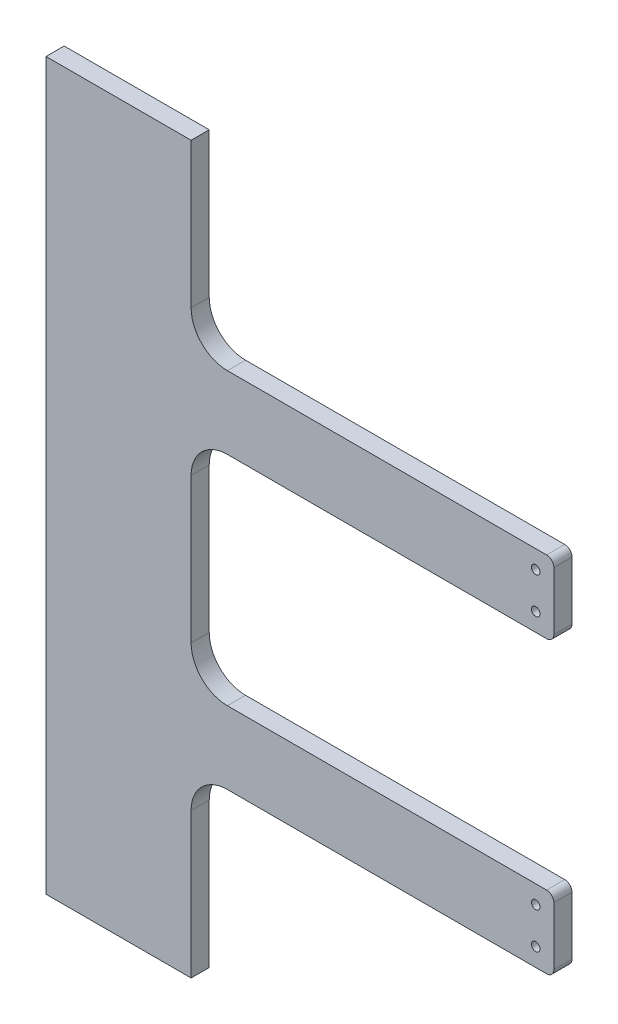
SolidWorks part; units mm, degrees
material "Pin"
ref_plane "Front" through (0, 0, 0) normal (0, 0, 1) x (1, 0, 0)
ref_plane "Top" through (0, 0, 0) normal (0, 1, 0) x (1, 0, 0)
ref_plane "Right" through (0, 0, 0) normal (1, 0, 0) x (0, 0, -1)
sketch "Esquisse1" plane through (0, 0, 0) normal (0, 0, 1) x (1, 0, 0)
  line L1 (-25.4, 127) -> (25.4, 127)
  line L2 (-25.4, 127) -> (-25.4, -127)
  line L3 (-25.4, -127) -> (25.4, -127)
  line L4 (25.4, 127) -> (25.4, -127)
  line L5 (-25.4, 127) -> (25.4, -127) construction
  line L6 (-25.4, -127) -> (25.4, 127) construction
  point P0 (0, 0)
  dimension "D1" = 254
  dimension "D2" = 50.8
extrude "Boss.-Extru.1" add sketch "Esquisse1" along normal blind 6.35
sketch "Esquisse2" plane through (0, 0, 6.35) normal (0, 0, 1) x (1, 0, 0)
  line L0 (25.4, -127) -> (25.4, 127) construction
  line L1 (25.4, -63.5) -> (152.4, -63.5)
  line L2 (25.4, -63.5) -> (25.4, -38.1)
  line L3 (25.4, -38.1) -> (152.4, -38.1)
  line L4 (152.4, -63.5) -> (152.4, -38.1)
  line L6 (-25.4, -127) -> (25.4, -127) construction
  line L7 (25.4, -38.1) -> (152.4, -63.5) construction
  line L8 (25.4, 38.1) -> (152.4, 38.1)
  line L9 (25.4, 38.1) -> (25.4, 63.5)
  line L10 (25.4, 63.5) -> (152.4, 63.5)
  line L11 (152.4, 38.1) -> (152.4, 63.5)
  line L12 (152.4, -38.1) -> (25.4, -63.5) construction
  line L13 (25.4, 63.5) -> (152.4, 38.1) construction
  line L14 (152.4, 63.5) -> (25.4, 38.1) construction
  point P12 (88.9, -50.8)
  point P13 (88.9, 50.8)
  dimension "D1" = 127
  dimension "D2" = 25.4
  dimension "D3" = 76.2
  dimension "D4" = 25.4
  dimension "D5" = 127
  dimension "D6" = 101.6
extrude "Boss.-Extru.2" add sketch "Esquisse2" against normal blind 6.35
fillet "Congé1" radius 12.7 4 edges at (25.4, -38.1, 3.175) (25.4, -63.5, 3.175) (25.4, 63.5, 3.175) (25.4, 38.1, 3.175)
fillet "Congé2" radius 2.54 4 edges at (152.4, 63.5, 3.175) (152.4, 38.1, 3.175) (152.4, -38.1, 3.175) (152.4, -63.5, 3.175)
sketch "Esquisse3" plane through (0, 0, 0) normal (0, 0, -1) x (-1, 0, 0)
  line L0 (-152.4, 40.64) -> (-152.4, 60.96) construction
  line L1 (-149.86, 63.5) -> (-38.1, 63.5) construction
  line L2 (-38.1, 38.1) -> (-149.86, 38.1) construction
  line L3 (-149.86, -38.1) -> (-38.1, -38.1) construction
  line L4 (-38.1, -63.5) -> (-149.86, -63.5) construction
  circle A0 centre (-146.05, 57.15) radius 1.5
  circle A1 centre (-146.05, 44.45) radius 1.5
  circle A2 centre (-146.05, -44.45) radius 1.5
  circle A3 centre (-146.05, -57.15) radius 1.5
  dimension "D1" = 3
  dimension "D2" = 3
  dimension "D3" = 3
  dimension "D4" = 3
  dimension "D5" = 6.35
  dimension "D6" = 6.35
  dimension "D7" = 6.35
  dimension "D8" = 6.35
  dimension "D9" = 6.35
extrude "Enlèv. mat.-Extru.1" cut sketch "Esquisse3" against normal through all
sketch "Esquisse6" plane through (0, 0, 0) normal (0, 0, -1) x (-1, 0, 0)
  line L0 (-25.4, 127) -> (25.4, 127) construction
  line L2 (25.4, 127) -> (25.4, -127) construction
  circle A0 centre (-15.875, 50.8) radius 1.9
  circle A1 centre (15.875, 50.8) radius 1.9
  circle A2 centre (-15.875, -50.8) radius 1.9
  circle A3 centre (15.875, -50.8) radius 1.9
  dimension "D1" = 3.8
  dimension "D2" = 3.8
  dimension "D3" = 3.8
  dimension "D4" = 3.8
  dimension "D5" = 76.2
  dimension "D6" = 101.6
  dimension "D7" = 31.75
  dimension "D8" = 31.75
  dimension "D9" = 9.525
  dimension "D10" = 9.525
